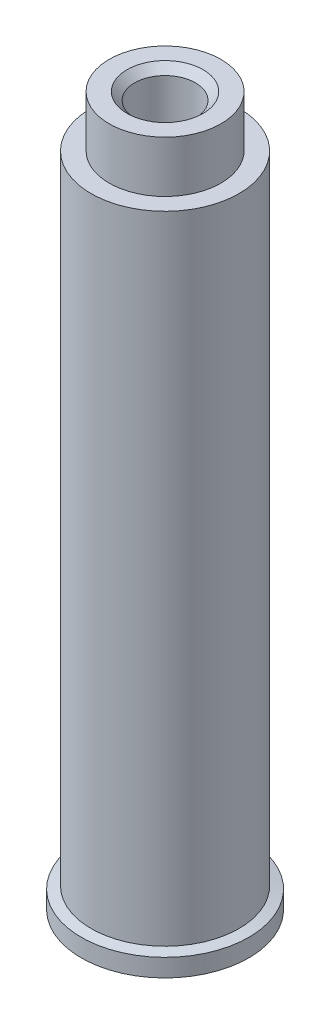
SolidWorks part; units mm, degrees
material "Ti-6Al-4VSolution treated and aged (SS)"
ref_plane "Front Plane" through (0, 0, 0) normal (0, 0, 1) x (1, 0, 0)
ref_plane "Top Plane" through (0, 0, 0) normal (0, 1, 0) x (1, 0, 0)
ref_plane "Right Plane" through (0, 0, 0) normal (1, 0, 0) x (0, 0, -1)
ref_axis "Axis1" through (0, -164.6103, 0) along (0, 1, 0)
sketch "Sketch1" plane through (0, 0, 0) normal (0, 0, 1) x (1, 0, 0)
  line L0 (3.9751, -11.938) -> (3.9751, 22.987)
  line L1 (3.9751, 22.987) -> (1.7272, 24.2848)
  line L2 (1.7272, 24.2848) -> (1.7272, 27.8892)
  line L3 (2.159, 28.321) -> (3.175, 28.321)
  line L4 (3.175, 28.321) -> (3.175, 25.4)
  line L5 (3.175, 25.4) -> (4.2037, 25.4)
  line L6 (4.2037, 25.4) -> (4.2037, -10.7723)
  line L7 (4.2037, -10.7723) -> (4.7625, -10.922)
  line L8 (4.7625, -10.922) -> (4.7625, -11.938)
  line L10 (4.7625, -11.938) -> (3.9751, -11.938)
  line L11 (0, -11.8137) -> (0, -19.3766) construction
  line L15 (2.159, 28.321) -> (1.7272, 27.8892)
  dimension "D1" = 3.4544
  dimension "D2" = 7.9502
  dimension "D3" = 6.35
  dimension "D4" = 8.4074
  dimension "D5" = 9.525
  dimension "D6" = 60
  dimension "D7" = 2.921
  dimension "D8" = 5.334
  dimension "D9" = 25.4
  dimension "D10" = 11.938
  dimension "D11" = 1.016
  dimension "D12" = 34.925
  dimension "D13" = 75
  dimension "D18" = 0.2286
  dimension "D19" = 45
  dimension "D20" = 4.318
revolve "Revolve1" add sketch "Sketch1" angle 360 about axis through (0, -164.6103, 0) along (0, 1, 0)
